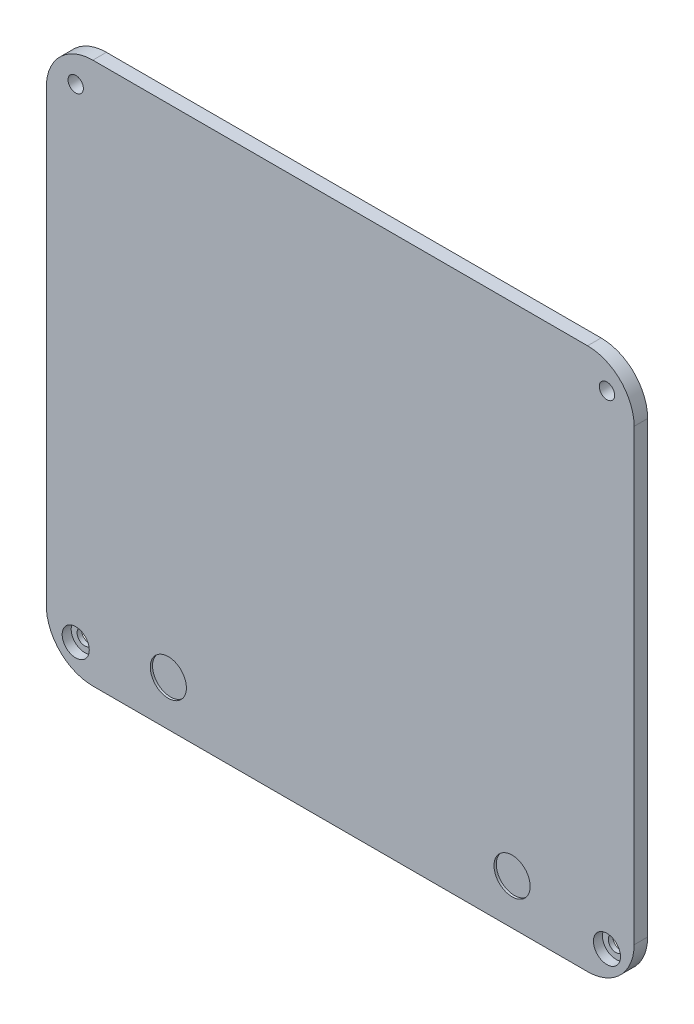
SolidWorks part; units mm, degrees
ref_plane "Ebene vorne" through (0, 0, 0) normal (0, 0, 1) x (1, 0, 0)
ref_plane "Ebene oben" through (0, 0, 0) normal (0, 1, 0) x (1, 0, 0)
ref_plane "Ebene rechts" through (0, 0, 0) normal (1, 0, 0) x (0, 0, -1)
sketch "Skizze1" plane through (0, 0, 0) normal (0, 0, 1) x (1, 0, 0)
  line L0 (-49.2275, -151.2967) -> (-49.2275, -51.8905) construction
  line L1 (-49.2275, -151.2967) -> (-49.2275, -51.8905)
  line L29 (-169.0581, -161.5967) -> (-59.5275, -161.5967) construction
  line L30 (-179.3474, -52.3842) -> (-179.3474, -150.8036) construction
  line L31 (-59.5275, -41.5905) -> (-169.0581, -41.5905) construction
  line L33 (-169.0581, -161.5967) -> (-59.5275, -161.5967)
  line L34 (-179.3474, -52.3842) -> (-179.3474, -150.8036)
  line L35 (-59.5275, -41.5905) -> (-169.0581, -41.5905)
  arc A0 (-59.5275, -161.5967) -> (-49.2275, -151.2967) centre (-59.5275, -151.2967) ccw construction
  arc A1 (-49.2275, -51.8905) -> (-59.5275, -41.5905) centre (-59.5275, -51.8905) ccw construction
  arc A2 (-59.5275, -161.5967) -> (-49.2275, -151.2967) centre (-59.5275, -151.2967) ccw
  arc A3 (-49.2275, -51.8905) -> (-59.5275, -41.5905) centre (-59.5275, -51.8905) ccw
  circle A35 centre (-172.8474, -155.0967) radius 1.7 construction
  circle A36 centre (-172.8474, -155.0967) radius 1.7
  circle A37 centre (-55.2338, -155.0967) radius 1.7 construction
  circle A38 centre (-55.2338, -155.0967) radius 1.7
  circle A39 centre (-55.2338, -48.0905) radius 1.7 construction
  circle A40 centre (-55.2338, -48.0905) radius 1.7
  circle A41 centre (-172.8474, -48.0905) radius 1.7 construction
  circle A42 centre (-172.8474, -48.0905) radius 1.7
  arc A45 (-179.3474, -150.8036) -> (-169.0581, -161.5967) centre (-169.0581, -151.2956) ccw construction
  arc A46 (-169.0581, -41.5905) -> (-179.3474, -52.3842) centre (-169.0581, -51.8916) ccw construction
  arc A49 (-179.3474, -150.8036) -> (-169.0581, -161.5967) centre (-169.0581, -151.2956) ccw
  arc A50 (-169.0581, -41.5905) -> (-179.3474, -52.3842) centre (-169.0581, -51.8916) ccw
extrude "Aufsatz-Linear austragen1" add sketch "Skizze1" along normal blind 3
sketch "Skizze2" plane through (0, 0, 3) normal (0, 0, 1) x (1, 0, 0)
  circle A0 centre (-172.8474, -155.0967) radius 3
  circle A1 centre (-55.2338, -155.0967) radius 3
  dimension "D1" = 6
  dimension "D2" = 6
extrude "Schnitt-Linear austragen1" cut sketch "Skizze2" against normal blind 2
sketch "Skizze3" plane through (0, 0, 3) normal (0, 0, 1) x (1, 0, 0)
  line L0 (-169.0581, -161.5967) -> (-59.5275, -161.5967) construction
  line L1 (-179.3474, -52.3842) -> (-179.3474, -150.8036) construction
  line L2 (-114.2928, -41.5905) -> (-114.2928, -161.5967) construction
  line L3 (-59.5275, -41.5905) -> (-169.0581, -41.5905) construction
  circle A0 centre (-152.3474, -151.5967) radius 4
  circle A1 centre (-76.2382, -151.5967) radius 4
  dimension "D1" = 8
  dimension "D2" = 10
  dimension "D3" = 27
extrude "Schnitt-Linear austragen2" cut sketch "Skizze3" against normal blind 0.5
